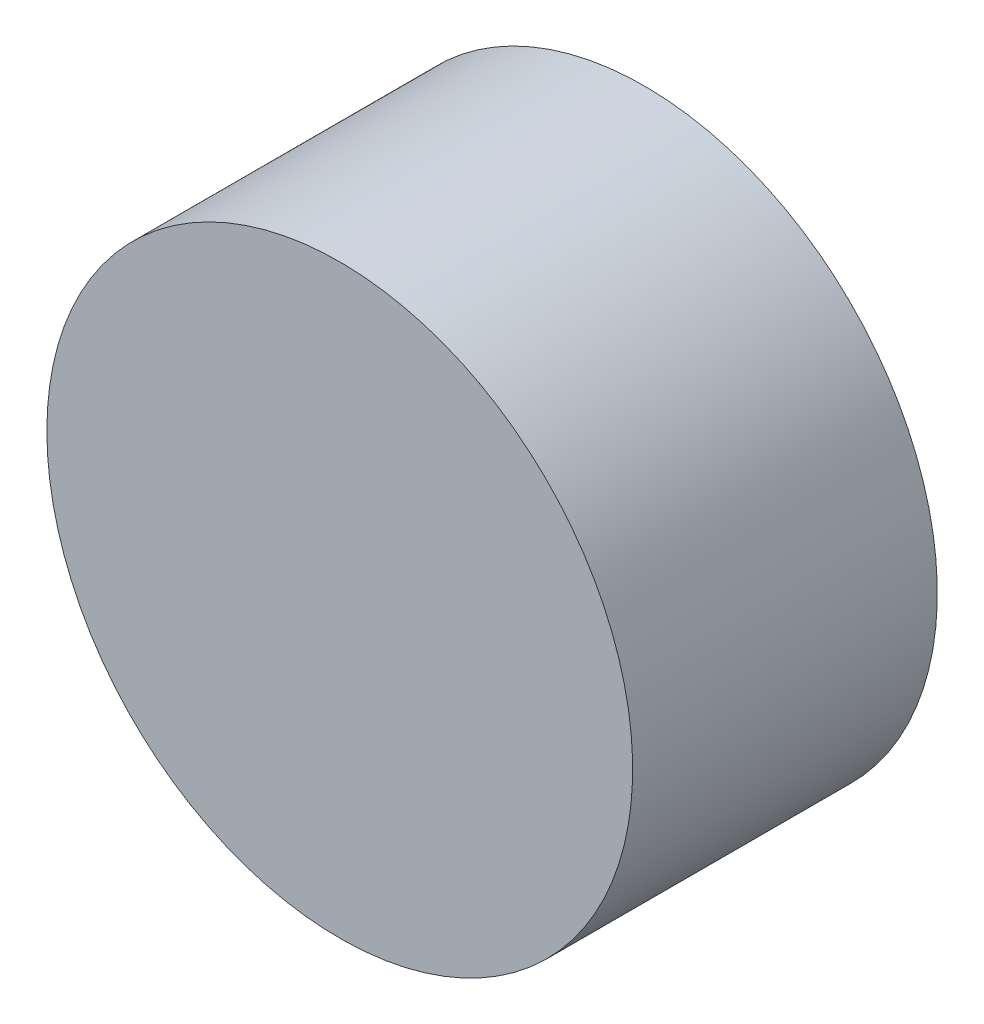
SolidWorks part; units mm, degrees
ref_plane "Płaszczyzna przednia" through (0, 0, 0) normal (0, 0, 1) x (1, 0, 0)
ref_plane "Płaszczyzna górna" through (0, 0, 0) normal (0, 1, 0) x (1, 0, 0)
ref_plane "Płaszczyzna prawa" through (0, 0, 0) normal (1, 0, 0) x (0, 0, -1)
sketch "Szkic1" plane through (0, 0, 0) normal (0, 0, 1) x (1, 0, 0)
  circle A0 centre (0, 0) radius 12.5
  dimension "D1" = 25
extrude "Dodanie-wyciągnięcie2" add sketch "Szkic1" along normal blind 13
sketch "Szkic2" plane through (0, 0, 0) normal (0, 0, -1) x (-1, 0, 0)
  circle A0 centre (0, 0) radius 3.175
  dimension "D1" = 6.35
extrude "Wytnij-wyciągnięcie1" cut sketch "Szkic2" against normal blind 12
sketch "Szkic3" plane through (0, 0, 12) normal (0, 0, -1) x (-1, 0, 0)
  line L0 (-3.1265, 0.5527) -> (3.1265, 0.5527)
  line L1 (3.1746, 0.0527) -> (-3.1746, 0.0527)
  circle A0 centre (0, 0) radius 3.175 construction
  circle A1 centre (0, 0) radius 3.175 construction
  dimension "D1" = 0.5
